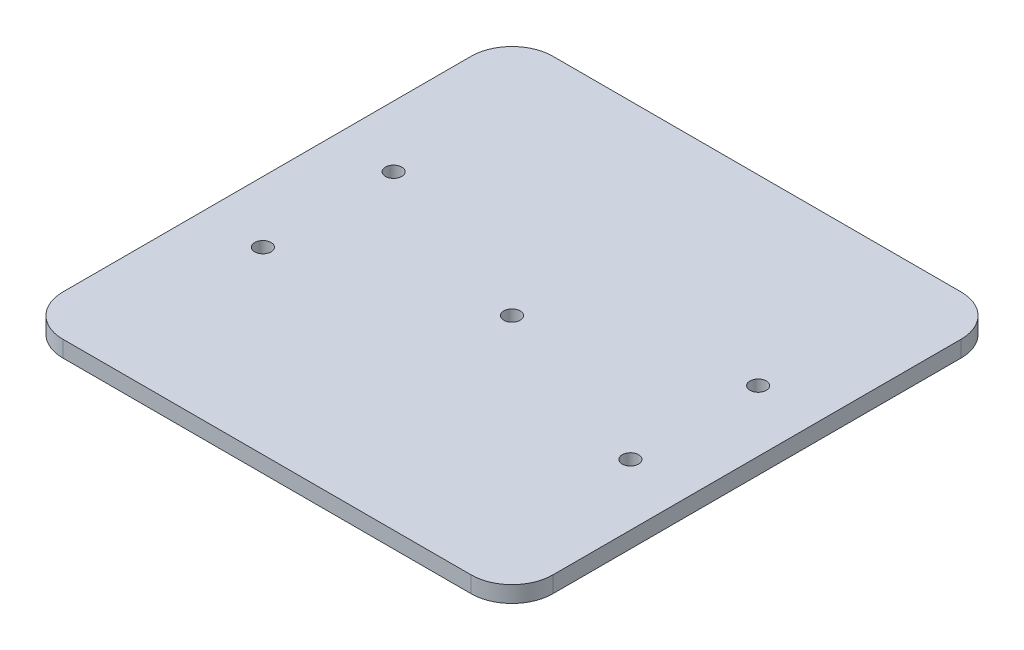
SolidWorks part; units mm, degrees
ref_plane "Front Plane" through (0, 0, 0) normal (0, 0, 1) x (1, 0, 0)
ref_plane "Top Plane" through (0, 0, 0) normal (0, 1, 0) x (1, 0, 0)
ref_plane "Right Plane" through (0, 0, 0) normal (1, 0, 0) x (0, 0, -1)
sketch "Sketch1" plane through (0, 0, 0) normal (0, 1, 0) x (1, 0, 0)
  line L1 (-25.219, 28.0292) -> (24.781, 28.0292)
  line L2 (-30.219, 23.0292) -> (-30.219, -26.9708)
  line L3 (-25.219, -31.9708) -> (24.781, -31.9708)
  line L4 (29.781, 23.0292) -> (29.781, -26.9708)
  arc A0 (24.781, 28.0292) -> (29.781, 23.0292) centre (24.781, 23.0292) cw
  arc A1 (24.781, -31.9708) -> (29.781, -26.9708) centre (24.781, -26.9708) ccw
  arc A2 (-30.219, -26.9708) -> (-25.219, -31.9708) centre (-25.219, -26.9708) ccw
  arc A3 (-25.219, 28.0292) -> (-30.219, 23.0292) centre (-25.219, 23.0292) ccw
  point P6 (29.781, 28.0292)
  point P11 (-30.219, -31.9708)
  point P14 (-30.219, 28.0292)
  dimension "D3" = 5
  dimension "D1" = 60
  dimension "D2" = 60
extrude "Boss-Extrude1" add sketch "Sketch1" along normal blind 2
sketch "Sketch2" plane through (0, 2, 0) normal (0, 1, 0) x (1, 0, 0)
  line L0 (24.781, 28.0292) -> (-25.219, 28.0292) construction
  line L1 (-25.219, -31.9708) -> (24.781, -31.9708) construction
  line L2 (29.781, -26.9708) -> (29.781, 23.0292) construction
  line L3 (-30.219, 23.0292) -> (-30.219, -26.9708) construction
  circle A1 centre (-22.719, 6.0292) radius 1
  circle A2 centre (-22.719, -9.9708) radius 1
  circle A3 centre (22.281, 5.6699) radius 1
  circle A4 centre (22.281, -9.9708) radius 1
  circle A5 centre (-0.219, -1.9708) radius 1
  point P10 (0, 0)
  point P17 (22.281, -9.9708)
  dimension "D1" = 22
  dimension "D2" = 22
  dimension "D3" = 7.5
  dimension "D4" = 7.5
  dimension "D5" = 7.5
  dimension "D6" = 30
  dimension "D7" = 30
extrude "Cut-Extrude1" cut sketch "Sketch2" against normal blind 3
